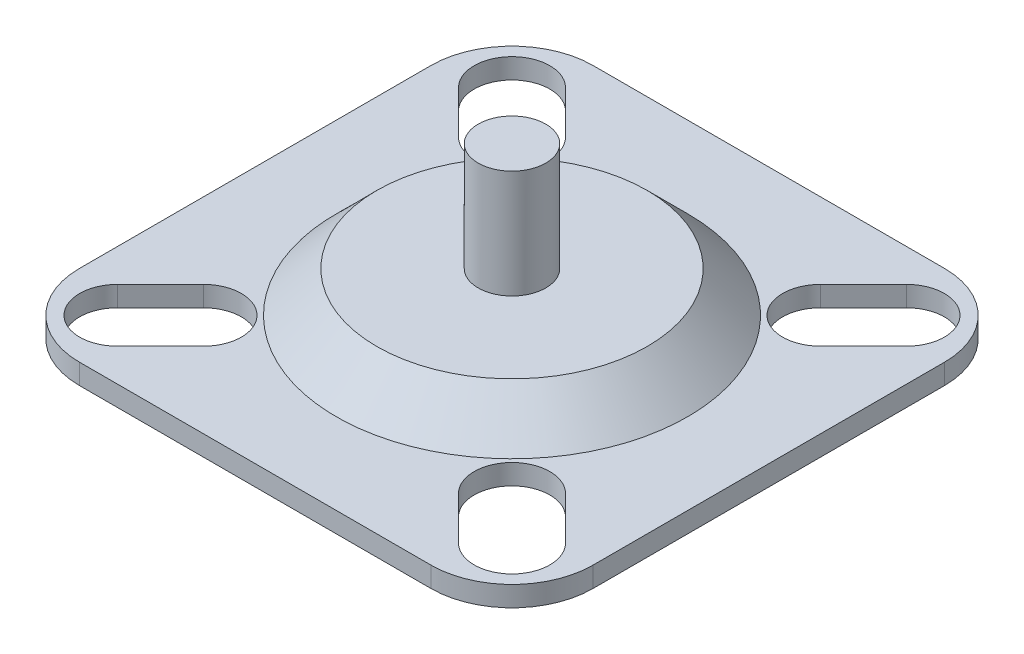
SolidWorks part; units mm, degrees
material "6061 Alloy"
ref_plane "Front Plane" through (0, 0, 0) normal (0, 0, 1) x (1, 0, 0)
ref_plane "Top Plane" through (0, 0, 0) normal (0, 1, 0) x (1, 0, 0)
ref_plane "Right Plane" through (0, 0, 0) normal (1, 0, 0) x (0, 0, -1)
sketch "Sketch1" plane through (0, 0, 0) normal (0, 1, 0) x (1, 0, 0)
  line L0 (-14.591, 14.591) -> (-11.409, 11.409) construction
  line L1 (-13, -19) -> (13, -19)
  line L2 (-19, -13) -> (-19, 13)
  line L3 (-13, 19) -> (13, 19)
  line L4 (19, -13) -> (19, 13)
  line L5 (-19, -19) -> (19, 19) construction
  line L6 (-19, 19) -> (19, -19) construction
  line L7 (-12.6111, 16.5709) -> (-9.4291, 13.3889)
  line L8 (-16.5709, 12.6111) -> (-13.3889, 9.4291)
  line L9 (14.591, 14.591) -> (11.409, 11.409) construction
  line L10 (16.5709, 12.6111) -> (13.3889, 9.4291)
  line L11 (12.6111, 16.5709) -> (9.4291, 13.3889)
  line L12 (14.591, -14.591) -> (11.409, -11.409) construction
  line L13 (12.6111, -16.5709) -> (9.4291, -13.3889)
  line L14 (16.5709, -12.6111) -> (13.3889, -9.4291)
  line L15 (-14.591, -14.591) -> (-11.409, -11.409) construction
  line L16 (-16.5709, -12.6111) -> (-13.3889, -9.4291)
  line L17 (-12.6111, -16.5709) -> (-9.4291, -13.3889)
  arc A0 (-13, -19) -> (-19, -13) centre (-13, -13) cw
  arc A1 (13, -19) -> (19, -13) centre (13, -13) ccw
  arc A2 (13, 19) -> (19, 13) centre (13, 13) cw
  arc A3 (-19, 13) -> (-13, 19) centre (-13, 13) cw
  arc A4 (-12.6111, 16.5709) -> (-16.5709, 12.6111) centre (-14.591, 14.591) ccw
  arc A5 (-13.3889, 9.4291) -> (-9.4291, 13.3889) centre (-11.409, 11.409) ccw
  arc A6 (16.5709, 12.6111) -> (12.6111, 16.5709) centre (14.591, 14.591) ccw
  arc A7 (9.4291, 13.3889) -> (13.3889, 9.4291) centre (11.409, 11.409) ccw
  arc A8 (12.6111, -16.5709) -> (16.5709, -12.6111) centre (14.591, -14.591) ccw
  arc A9 (13.3889, -9.4291) -> (9.4291, -13.3889) centre (11.409, -11.409) ccw
  arc A10 (-16.5709, -12.6111) -> (-12.6111, -16.5709) centre (-14.591, -14.591) ccw
  arc A11 (-9.4291, -13.3889) -> (-13.3889, -9.4291) centre (-11.409, -11.409) ccw
  point P0 (0, 0)
  point P20 (-13, 13)
  point P30 (13, 13)
  point P37 (13, -13)
  point P44 (-13, -13)
  point P49 (0, 0)
  dimension "D3" = 6
  dimension "D5" = 2.8
  dimension "D1" = 38
  dimension "D2" = 38
  dimension "D4" = 4.5
  dimension "D6" = 0
  dimension "D7" = 4
extrude "Boss-Extrude1" add sketch "Sketch1" along normal blind 1.5
sketch "Sketch3" plane through (0, 0, 0) normal (1, 0, 0) x (0, 0, -1)
  line L0 (0, 1.5) -> (13, 1.5)
  line L1 (-13, 1.5) -> (13, 1.5) construction
  line L2 (13, 1.5) -> (10, 4.5)
  line L3 (10, 4.5) -> (0, 4.5)
  line L4 (0, 4.5) -> (0, 1.5)
  dimension "D1" = 10
  dimension "D2" = 3
  dimension "D3" = 13
revolve "Revolve1" add sketch "Sketch3" angle 360 about L4
sketch "Sketch4" plane through (0, 0, 0) normal (1, 0, 0) x (0, 0, -1)
  line L0 (0, 0) -> (12, 0)
  line L1 (-13, 0) -> (13, 0) construction
  line L2 (12, 0) -> (8, 4)
  line L3 (8, 4) -> (0, 4)
  line L4 (0, 4) -> (0, 0)
  line L5 (10, 4.5) -> (-10, 4.5) construction
  point P5 (8.4509, 3.5491)
  dimension "D1" = 12
  dimension "D2" = 0.5
  dimension "D4" = 8
revolve "Cut-Revolve1" cut sketch "Sketch4" angle 360 about L4
fillet "Fillet1" radius 1 2 edges at (0, 0, 12) (0, 4, 8)
sketch "Sketch5" plane through (0, 4.5, 0) normal (0, 1, 0) x (1, 0, 0)
  circle A0 centre (0, 0) radius 2.5
  dimension "D1" = 5
extrude "Boss-Extrude2" add sketch "Sketch5" along normal blind 8
